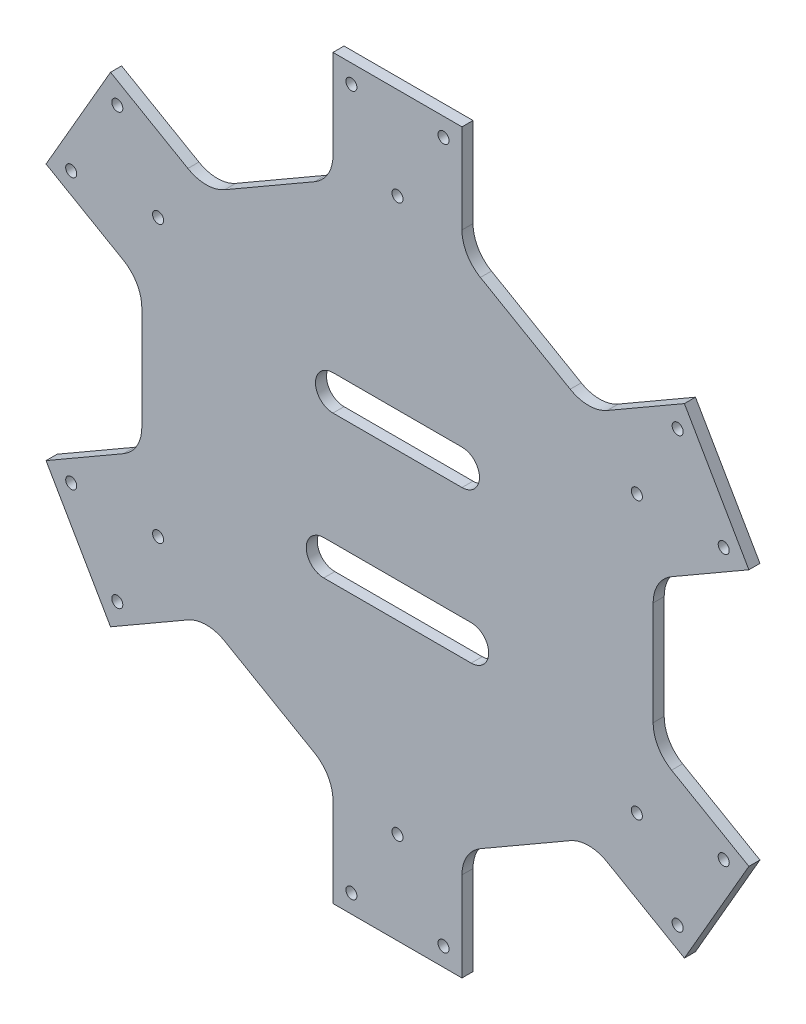
SolidWorks part; units mm, degrees
ref_plane "Ön Düzlem" through (0, 0, 0) normal (0, 0, 1) x (1, 0, 0)
ref_plane "Üst Düzlem" through (0, 0, 0) normal (0, 1, 0) x (1, 0, 0)
ref_plane "Sağ Düzlem" through (0, 0, 0) normal (1, 0, 0) x (0, 0, -1)
sketch "Çizim1" plane through (0, 0, 0) normal (0, 0, 1) x (1, 0, 0)
  line L0 (-17.5, 100) -> (17.5, 100)
  line L2 (17.5, 100) -> (-17.5, 100)
  line L3 (-77.8525, 65.1554) -> (-95.3525, 34.8446)
  line L4 (-95.3525, -34.8446) -> (-77.8525, -65.1554)
  line L5 (-17.5, -100) -> (17.5, -100)
  line L6 (77.8525, -65.1554) -> (95.3525, -34.8446)
  line L7 (-17.5, 100) -> (-17.5, 75.7735)
  line L8 (17.5, 100) -> (17.5, 75.7735)
  line L9 (95.3525, 34.8446) -> (74.3718, 22.7313)
  line L10 (77.8525, 65.1554) -> (95.3525, 34.8446)
  line L11 (77.8525, 65.1554) -> (56.8718, 53.0422)
  line L12 (77.8525, -65.1554) -> (56.8718, -53.0422)
  line L13 (95.3525, -34.8446) -> (77.8525, -65.1554)
  line L14 (95.3525, -34.8446) -> (74.3718, -22.7313)
  line L15 (-17.5, -100) -> (-17.5, -75.7735)
  line L16 (17.5, -100) -> (-17.5, -100)
  line L17 (17.5, -100) -> (17.5, -75.7735)
  line L18 (-95.3525, -34.8446) -> (-74.3718, -22.7313)
  line L19 (-77.8525, -65.1554) -> (-95.3525, -34.8446)
  line L20 (-77.8525, -65.1554) -> (-56.8718, -53.0422)
  line L21 (-77.8525, 65.1554) -> (-56.8718, 53.0422)
  line L22 (-95.3525, 34.8446) -> (-77.8525, 65.1554)
  line L23 (-95.3525, 34.8446) -> (-74.3718, 22.7313)
  line L24 (0, 0) -> (17.5, 70) construction
  line L25 (0, 0) -> (69.3718, 19.8446) construction
  line L26 (-46.8718, 53.0422) -> (-22.5, 67.1132)
  line L27 (22.5, 67.1132) -> (46.8718, 53.0422)
  line L28 (69.3718, 14.0711) -> (69.3718, -14.0711)
  line L29 (46.8718, -53.0422) -> (22.5, -67.1132)
  line L30 (-22.5, -67.1132) -> (-46.8718, -53.0422)
  line L31 (-69.3718, -14.0711) -> (-69.3718, 14.0711)
  line L32 (115.4701, 0) -> (95.3525, 34.8446) [skipped]
  line L34 (-17.5, 100) -> (-12.5, 100)
  line L35 (-17.5, 100) -> (-17.5, 95)
  line L38 (17.5, 100) -> (12.5, 100)
  line L39 (17.5, 100) -> (17.5, 95)
  circle A0 centre (-12.5, 95) radius 1.5
  arc A1 (-56.8718, 53.0422) -> (-46.8718, 53.0422) centre (-51.8718, 61.7024) ccw
  arc A2 (-22.5, 67.1132) -> (-17.5, 75.7735) centre (-27.5, 75.7735) ccw
  arc A3 (17.5, 75.7735) -> (22.5, 67.1132) centre (27.5, 75.7735) ccw
  arc A4 (46.8718, 53.0422) -> (56.8718, 53.0422) centre (51.8718, 61.7024) ccw
  arc A5 (74.3718, 22.7313) -> (69.3718, 14.0711) centre (79.3718, 14.0711) ccw
  arc A6 (69.3718, -14.0711) -> (74.3718, -22.7313) centre (79.3718, -14.0711) ccw
  arc A7 (56.8718, -53.0422) -> (46.8718, -53.0422) centre (51.8718, -61.7024) ccw
  arc A8 (22.5, -67.1132) -> (17.5, -75.7735) centre (27.5, -75.7735) ccw
  arc A9 (-17.5, -75.7735) -> (-22.5, -67.1132) centre (-27.5, -75.7735) ccw
  arc A10 (-46.8718, -53.0422) -> (-56.8718, -53.0422) centre (-51.8718, -61.7024) ccw
  arc A11 (-74.3718, -22.7313) -> (-69.3718, -14.0711) centre (-79.3718, -14.0711) ccw
  arc A12 (-74.3718, 22.7313) -> (-69.3718, 14.0711) centre (-79.3718, 14.0711) cw
  circle A13 centre (12.5, 95) radius 1.5
  circle A14 centre (0, 75) radius 1.5
  circle A15 centre (76.0224, 58.3253) radius 1.5
  circle A16 centre (88.5224, 36.6747) radius 1.5
  circle A17 centre (64.9519, 37.5) radius 1.5
  circle A18 centre (88.5224, -36.6747) radius 1.5
  circle A19 centre (76.0224, -58.3253) radius 1.5
  circle A20 centre (64.9519, -37.5) radius 1.5
  circle A21 centre (12.5, -95) radius 1.5
  circle A22 centre (-12.5, -95) radius 1.5
  circle A23 centre (0, -75) radius 1.5
  circle A24 centre (-76.0224, -58.3253) radius 1.5
  circle A25 centre (-88.5224, -36.6747) radius 1.5
  circle A26 centre (-64.9519, -37.5) radius 1.5
  circle A27 centre (-88.5224, 36.6747) radius 1.5
  circle A28 centre (-76.0224, 58.3253) radius 1.5
  circle A29 centre (-64.9519, 37.5) radius 1.5
  point P12 (0, 100)
  point P19 (86.6025, 50)
  point P24 (86.6025, -50)
  point P29 (0, -100)
  point P34 (-86.6025, -50)
  point P39 (-86.6025, 50)
  point P48 (17.5, 70)
  point P53 (69.3718, 19.8446)
  point P105 (0, 0)
  dimension "D3" = 10
  dimension "D4" = 6
  dimension "D1" = 6
  dimension "D2" = 60
extrude "Yükseklik-Ekstrüzyon1" add sketch "Çizim1" along normal blind 3 contours L23 A12 L31 A11 L18 L4 L20 A10 L30 A9 L15 L5 L17 A8 L29 A7 L12 L6 L14 A6 L28 A5 L9 L10 L11 A4 L27 A3 L8 L0 L2 L7 A2 L26 A1 L21 L3 A29 A28 A27 A26 A25
sketch "Çizim2" plane through (0, 0, 3) normal (0, 0, 1) x (1, 0, 0)
  line L0 (0, 20) -> (0, -20)
  line L1 (-17.5, 20) -> (17.5, 20) construction
  line L2 (-17.5, 24.75) -> (17.5, 24.75)
  line L3 (-17.5, 15.25) -> (17.5, 15.25)
  line L4 (-20, -20) -> (20, -20) construction
  line L5 (-20, -15.25) -> (20, -15.25)
  line L6 (-20, -24.75) -> (20, -24.75)
  arc A0 (-17.5, 24.75) -> (-17.5, 15.25) centre (-17.5, 20) ccw
  arc A1 (17.5, 15.25) -> (17.5, 24.75) centre (17.5, 20) ccw
  arc A2 (-20, -15.25) -> (-20, -24.75) centre (-20, -20) ccw
  arc A3 (20, -24.75) -> (20, -15.25) centre (20, -20) ccw
  point P4 (0, 0)
  point P7 (0, 20)
  point P14 (0, -20)
extrude "Kes-Ekstrüzyon2" cut sketch "Çizim2" against normal blind 3 contours L3 A1 L2 A0 | L6 A3 L5 A2
